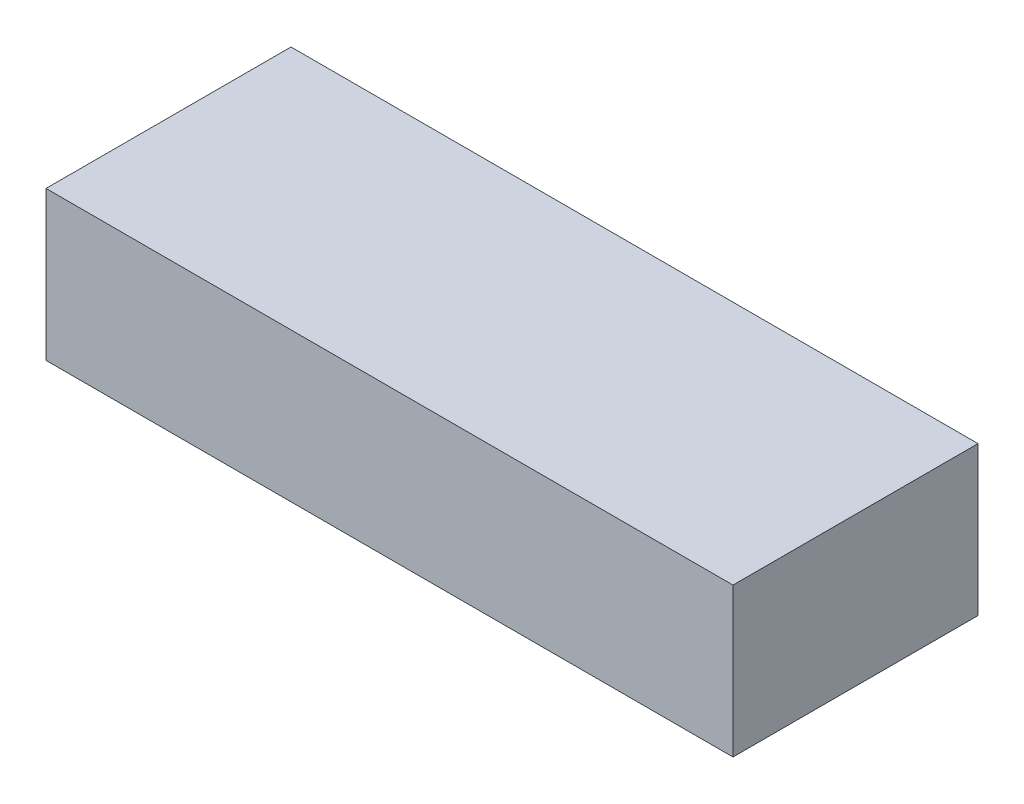
SolidWorks part; units mm, degrees
material "Manual Density from Real Component Battery 4000"
ref_plane "Piano frontale" through (0, 0, 0) normal (0, 0, 1) x (1, 0, 0)
ref_plane "Piano superiore" through (0, 0, 0) normal (0, 1, 0) x (1, 0, 0)
ref_plane "Piano destro" through (0, 0, 0) normal (1, 0, 0) x (0, 0, -1)
sketch "Schizzo1" plane through (0, 0, 0) normal (0, 1, 0) x (1, 0, 0)
  line L1 (71.5, -25.5) -> (-71.5, -25.5)
  line L2 (71.5, -25.5) -> (71.5, 25.5)
  line L3 (71.5, 25.5) -> (-71.5, 25.5)
  line L4 (-71.5, -25.5) -> (-71.5, 25.5)
  line L5 (71.5, -25.5) -> (-71.5, 25.5) construction
  line L6 (71.5, 25.5) -> (-71.5, -25.5) construction
  point P0 (0, 0)
  dimension "D1" = 51
  dimension "D2" = 143
extrude "Estrusione-Estrusione1" add sketch "Schizzo1" along normal blind 31
